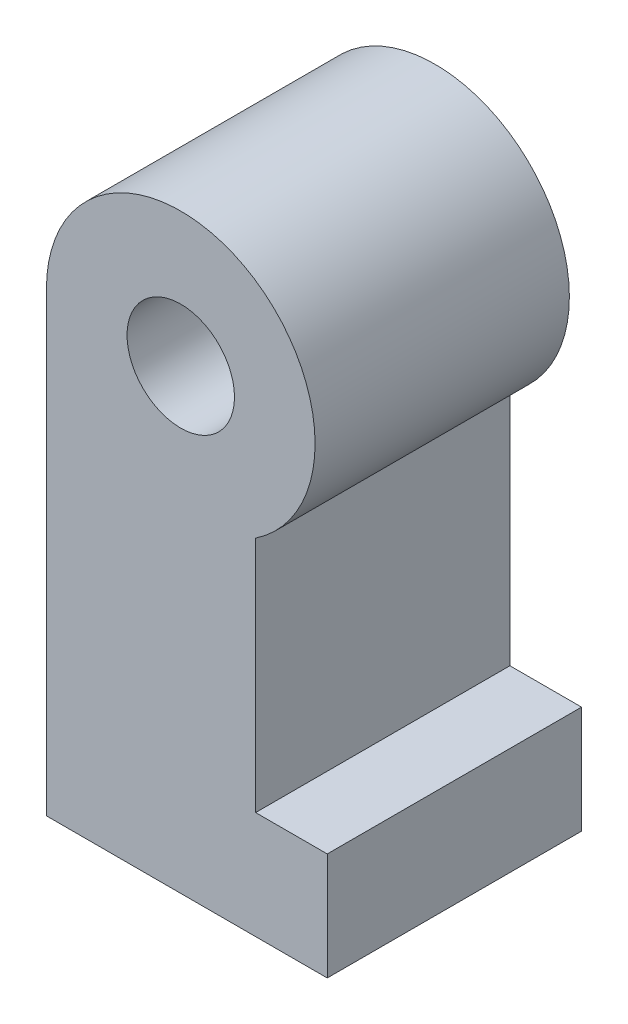
SolidWorks part; units mm, degrees
ref_plane "Front Plane" through (0, 0, 0) normal (0, 0, 1) x (1, 0, 0)
ref_plane "Top Plane" through (0, 0, 0) normal (0, 1, 0) x (1, 0, 0)
ref_plane "Right Plane" through (0, 0, 0) normal (1, 0, 0) x (0, 0, -1)
sketch "Sketch1" plane through (0, 0, 0) normal (0, 0, 1) x (1, 0, 0)
  line L0 (-95.25, 0) -> (-95.25, -323.85)
  line L1 (-95.25, -323.85) -> (103.886, -323.85)
  line L2 (103.886, -323.85) -> (103.886, -247.65)
  line L3 (103.886, -247.65) -> (53.086, -247.65)
  line L4 (53.086, -247.65) -> (53.086, -79.085)
  arc A0 (53.086, -79.085) -> (-95.25, 0) centre (0, 0) ccw
  dimension "D1" = 190.5
  dimension "D2" = 323.85
  dimension "D3" = 199.136
  dimension "D4" = 76.2
  dimension "D5" = 50.8
extrude "Boss-Extrude1" add sketch "Sketch1" along normal blind 180.34
sketch "Sketch2" plane through (0, 0, 180.34) normal (0, 0, 1) x (1, 0, 0)
  circle A0 centre (0, 0) radius 38.1
  dimension "D1" = 76.2
extrude "Cut-Extrude1" cut sketch "Sketch2" against normal blind 101.6
sketch "Sketch3" plane through (0, -323.85, 0) normal (0, -1, 0) x (1, 0, 0)
  line L0 (-95.25, 180.34) -> (103.886, 180.34) construction
  line L1 (-95.25, 180.34) -> (-95.25, 0) construction
  circle A0 centre (0, 90.17) radius 61.722
  dimension "D1" = 123.444
  dimension "D2" = 90.17
  dimension "D3" = 95.25
extrude "Cut-Extrude2" cut sketch "Sketch3" against normal blind 50.8
sketch "Sketch4" plane through (-95.25, 0, 0) normal (-1, 0, 0) x (0, 0, 1)
  line L0 (0, 0) -> (0, -323.85) construction
  line L1 (180.34, -323.85) -> (0, -323.85) construction
  circle A0 centre (90.17, -209.55) radius 61.722
  circle A1 centre (90.17, -9.906) radius 61.722
  dimension "D1" = 123.444
  dimension "D2" = 90.17
  dimension "D3" = 114.3
  dimension "D4" = 2
extrude "Cut-Extrude8" cut sketch "Sketch4" against normal blind 50.8
